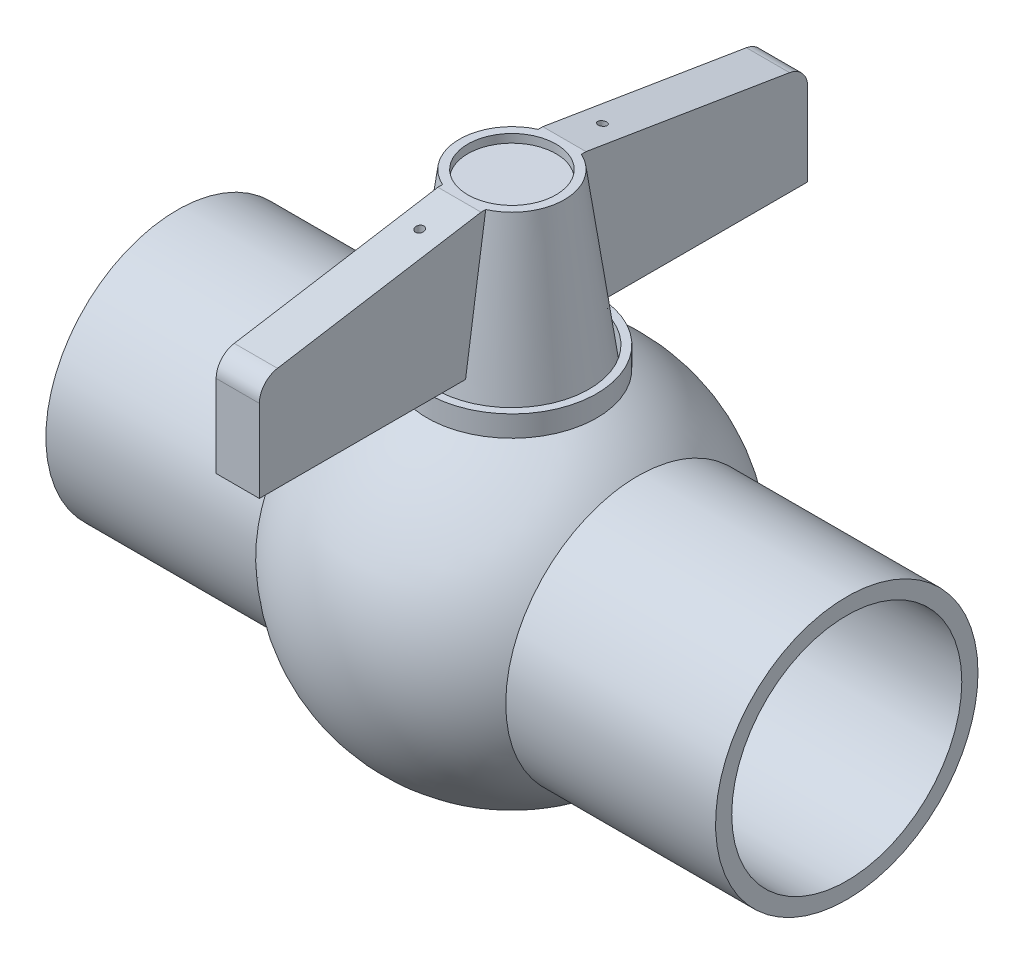
SolidWorks part; units mm, degrees
material "PVC Rígido"
ref_plane "Alzado" through (0, 0, 0) normal (0, 0, 1) x (1, 0, 0)
ref_plane "Planta" through (0, 0, 0) normal (0, 1, 0) x (1, 0, 0)
ref_plane "Vista lateral" through (0, 0, 0) normal (1, 0, 0) x (0, 0, -1)
sketch "Croquis1" plane through (0, 0, 0) normal (1, 0, 0) x (0, 0, -1)
  circle A0 centre (0, 0) radius 10.65
  circle A1 centre (0, 0) radius 12.15
  dimension "D1" = 21.3
  dimension "D2" = 24.3
extrude "Saliente-Extruir1" add sketch "Croquis1" along normal blind 62
ref_plane "Plano1" through (31, 0, 0) normal (1, 0, 0) x (0, 0, -1)
sketch "Croquis2" plane through (31, 0, 0) normal (1, 0, 0) x (0, 0, -1)
  line L0 (0, -16.7129) -> (0, 16.8536) construction
  line L1 (0, 16.8536) -> (7.8554, 16.8536) construction
  line L2 (7.8554, 16.8536) -> (7.8554, 14.9017)
  line L3 (7.8554, 16.8536) -> (7.1413, 16.8536)
  line L4 (7.1413, 16.8536) -> (7.1413, 12.6833)
  line L5 (7.1413, 12.6833) -> (0, 12.6833)
  line L6 (0, -16.7129) -> (0, 12.6833)
  arc A2 (0, -16.7129) -> (7.8554, 14.9017) centre (0, 0.0704) ccw
revolve "Revolución1" add sketch "Croquis2" angle 360 about L6
ref_plane "Plano2" through (31, 0, 0) normal (-1, 0, 0) x (0, 0, 1)
sketch "Croquis3" plane through (31, 0, 0) normal (-1, 0, 0) x (0, 0, 1)
  line L0 (0, 14.9017) -> (-7.0579, 14.9017)
  line L1 (-7.8554, 14.9017) -> (7.8554, 14.9017) construction
  line L2 (-7.0579, 14.9017) -> (-4.8563, 30.9048)
  line L3 (-4.8563, 30.9048) -> (-4.0793, 30.9048)
  line L4 (-4.0793, 30.9048) -> (-4.0793, 30.1278)
  line L5 (-4.0793, 30.1278) -> (0, 30.1278)
  line L6 (0, 30.1278) -> (0, 14.9017) construction
  line L7 (0, 14.9017) -> (0, 30.1278)
revolve "Revolución2" add sketch "Croquis3" angle 360 about L6
sketch "Croquis4" plane through (31, 0, 0) normal (-1, 0, 0) x (0, 0, 1)
  line L0 (-4.8563, 30.9048) -> (-23.7063, 27.8127)
  line L1 (-25.3825, 25.8391) -> (-25.3825, 18.2135)
  line L2 (0, 30.9048) -> (0, 14.9017) construction
  line L4 (4.8563, 30.9048) -> (-4.8563, 30.9048) construction
  line L5 (-7.8554, 14.9017) -> (7.8554, 14.9017) construction
  line L6 (-25.3825, 18.2135) -> (25.3825, 18.2135)
  line L7 (-4.8563, 30.9048) -> (-4.0793, 30.9048)
  line L8 (25.3825, 25.8391) -> (25.3825, 18.2135)
  line L9 (4.8563, 30.9048) -> (23.7063, 27.8127)
  line L10 (4.0793, 30.1278) -> (-4.0793, 30.1278) construction
  line L11 (4.0793, 30.1278) -> (-4.0793, 30.1278)
  line L12 (-4.0793, 30.1278) -> (-4.0793, 30.9048)
  line L13 (4.0793, 30.1278) -> (4.0793, 30.9048)
  line L14 (4.0793, 30.9048) -> (4.8563, 30.9048)
  arc A0 (-23.7063, 27.8127) -> (-25.3825, 25.8391) centre (-23.3825, 25.8391) ccw
  arc A1 (23.7063, 27.8127) -> (25.3825, 25.8391) centre (23.3825, 25.8391) cw
  point P15 (0, 18.2135)
  dimension "D1" = 2
extrude "Saliente-Extruir2" add sketch "Croquis4" along normal blind 2 and the other way blind 2
sketch "Croquis7" plane through (62, 0, 0) normal (1, 0, 0) x (0, 0, -1)
  circle A0 centre (0, 0) radius 10.65 construction
  circle A1 centre (0, 0) radius 10.65
extrude "Cortar-Extruir1" cut sketch "Croquis7" against normal through all
ref_plane "Plano3" through (0, 30.9048, 0) normal (0, 1, 0) x (1, 0, 0)
sketch "Croquis8" plane through (0, 30.9048, 0) normal (0, 1, 0) x (1, 0, 0)
  line L0 (26.9207, 0) -> (35.0793, 0) construction
  circle A0 centre (30.9133, 8.465) radius 0.385
  circle A1 centre (30.9233, -8.465) radius 0.385
  circle A2 centre (31, 0) radius 4.0793 construction
  dimension "D2" = 0.77
  dimension "D3" = 0.77
  dimension "D1" = 16.93
  dimension "D4" = 8.465
extrude "Cortar-Extruir2" cut sketch "Croquis8" against normal up to surface (12.6913 mm away) up to face at (31, 18.2135, 15.9148)
